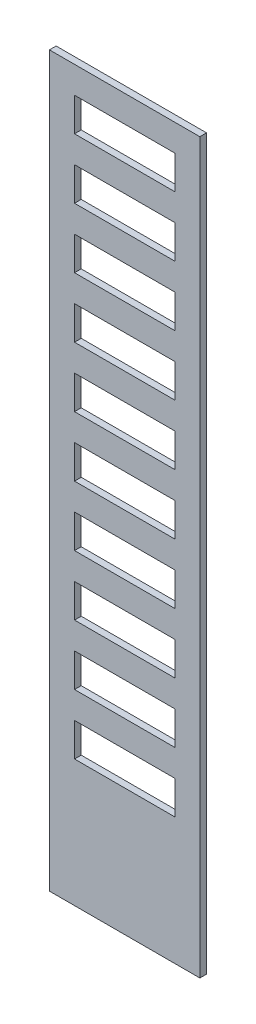
SolidWorks part; units mm, degrees
ref_plane "Front Plane" through (0, 0, 0) normal (0, 0, 1) x (1, 0, 0)
ref_plane "Top Plane" through (0, 0, 0) normal (0, 1, 0) x (1, 0, 0)
ref_plane "Right Plane" through (0, 0, 0) normal (1, 0, 0) x (0, 0, -1)
sketch "Sketch1" plane through (0, 0, 0) normal (0, 0, 1) x (1, 0, 0)
  line L0 (-22.5, -94) -> (-15, -94)
  line L1 (-22.5, -94) -> (22.5, -94)
  line L2 (-22.5, -94) -> (-22.5, 94)
  line L3 (-22.5, 94) -> (22.5, 94)
  line L4 (22.5, -94) -> (22.5, 94)
  line L5 (0, 94) -> (0, -94) construction
  line L6 (-22.5, 0) -> (22.5, 0) construction
  line L7 (-15, -94) -> (15, -94)
  line L8 (-22.5, -94) -> (-22.5, -86)
  line L9 (-22.5, -86) -> (-22.5, -76)
  line L10 (-22.5, -76) -> (-22.5, -68)
  line L11 (-22.5, -68) -> (-22.5, -58)
  line L12 (-22.5, -58) -> (-22.5, -50)
  line L13 (-22.5, -50) -> (-22.5, -40)
  line L14 (-22.5, -40) -> (-22.5, -32)
  line L15 (-22.5, -32) -> (-22.5, -22)
  line L16 (-22.5, -22) -> (-22.5, -14)
  line L17 (-22.5, -14) -> (-22.5, -4)
  line L18 (-22.5, -4) -> (-22.5, 4)
  line L19 (-22.5, 4) -> (-22.5, 14)
  line L20 (-22.5, 14) -> (-22.5, 22)
  line L21 (-22.5, 22) -> (-22.5, 32)
  line L22 (-22.5, 32) -> (-22.5, 40)
  line L23 (-22.5, 40) -> (-22.5, 50)
  line L24 (-22.5, 50) -> (-22.5, 58)
  line L25 (-22.5, 58) -> (-22.5, 68)
  line L26 (-22.5, 68) -> (-22.5, 76)
  line L27 (-22.5, 76) -> (-22.5, 86)
  line L28 (-15, -94) -> (-15, 94)
  line L29 (15, -94) -> (15, 94)
  line L30 (-22.5, -86) -> (22.5, -86)
  line L31 (-22.5, -76) -> (22.5, -76)
  line L32 (-22.5, -68) -> (22.5, -68)
  line L33 (-22.5, -58) -> (22.5, -58)
  line L34 (-22.5, -50) -> (22.5, -50)
  line L35 (-22.5, -40) -> (22.5, -40)
  line L36 (22.5, -40) -> (-22.5, -40)
  line L37 (-22.5, -32) -> (22.5, -32)
  line L38 (-22.5, -22) -> (22.5, -22)
  line L39 (-22.5, -14) -> (22.5, -14)
  line L40 (-22.5, -4) -> (22.5, -4)
  line L41 (-22.5, 4) -> (22.5, 4)
  line L42 (-22.5, 14) -> (22.5, 14)
  line L43 (-22.5, 22) -> (22.5, 22)
  line L44 (-22.5, 32) -> (22.5, 32)
  line L45 (-22.5, 40) -> (22.5, 40)
  line L46 (-22.5, 50) -> (22.5, 50)
  line L47 (-22.5, 58) -> (22.5, 58)
  line L48 (-22.5, 68) -> (22.5, 68)
  line L49 (-22.5, 76) -> (22.5, 76)
  line L50 (-22.5, 86) -> (22.5, 86)
  point P0 (0, 0)
  dimension "D1" = 188
  dimension "D2" = 45
  dimension "D3" = 7.5
  dimension "D4" = 7.5
  dimension "D5" = 30
  dimension "D6" = 8
  dimension "D7" = 10
  dimension "D8" = 8
  dimension "D9" = 10
  dimension "D10" = 8
  dimension "D11" = 10
  dimension "D12" = 8
  dimension "D13" = 10
  dimension "D14" = 8
  dimension "D15" = 10
  dimension "D16" = 8
  dimension "D17" = 10
  dimension "D18" = 8
  dimension "D19" = 10
  dimension "D20" = 8
  dimension "D21" = 10
  dimension "D22" = 8
  dimension "D23" = 10
  dimension "D24" = 8
  dimension "D25" = 10
  dimension "D26" = 8
extrude "Boss-Extrude1" add sketch "Sketch1" along normal blind 2 contours L2 L50 L28 L3 | L50 L2 L49 L28 | L49 L2 L48 L28 | L48 L2 L47 L28 | L47 L2 L46 L28 | L46 L2 L45 L28 | L28 L50 L29 L3 | L29 L50 L4 L3 | L50 L29 L49 L4 | L49 L29 L48 L4 | L49 L28 L48 L29 | L47 L28 L46 L29 | L47 L29 L46 L4 | L48 L29 L47 L4 | L46 L29 L45 L4 | L45 L29 L44 L4 | L45 L28 L44 L29 | L45 L2 L44 L28 | L44 L2 L43 L28 | L43 L2 L42 L28 | L42 L2 L41 L28 | L41 L2 L40 L28 | L41 L28 L40 L29 | L41 L29 L40 L4 | L42 L29 L41 L4 | L43 L29 L42 L4 | L43 L28 L42 L29 | L44 L29 L43 L4 | L40 L2 L39 L28 | L39 L2 L38 L28 | L38 L2 L37 L28 | L37 L2 L35 L28 | L35 L2 L34 L28 | L37 L28 L35 L29 | L39 L28 L38 L29 | L39 L29 L38 L4 | L40 L29 L39 L4 | L38 L29 L37 L4 | L37 L29 L35 L4 | L34 L2 L33 L28 | L33 L2 L32 L28 | L32 L2 L31 L28 | L31 L2 L30 L28 | L30 L2 L0 L28 | L30 L28 L1 L29 | L30 L29 L1 L4 | L31 L29 L30 L4 | L32 L29 L31 L4 | L33 L29 L32 L4 | L34 L29 L33 L4 | L35 L29 L34 L4 | L34 L28 L33 L29 | L32 L28 L31 L29
sketch "Sketch2" plane through (0, 0, 2) normal (0, 0, 1) x (1, 0, 0)
  line L1 (-22.5, -94) -> (22.5, -94)
  line L2 (-22.5, -94) -> (-22.5, -124)
  line L3 (-22.5, -124) -> (22.5, -124)
  line L4 (22.5, -94) -> (22.5, -124)
  dimension "D1" = 30
  dimension "D2" = 45
extrude "Boss-Extrude2" add sketch "Sketch2" against normal blind 2
